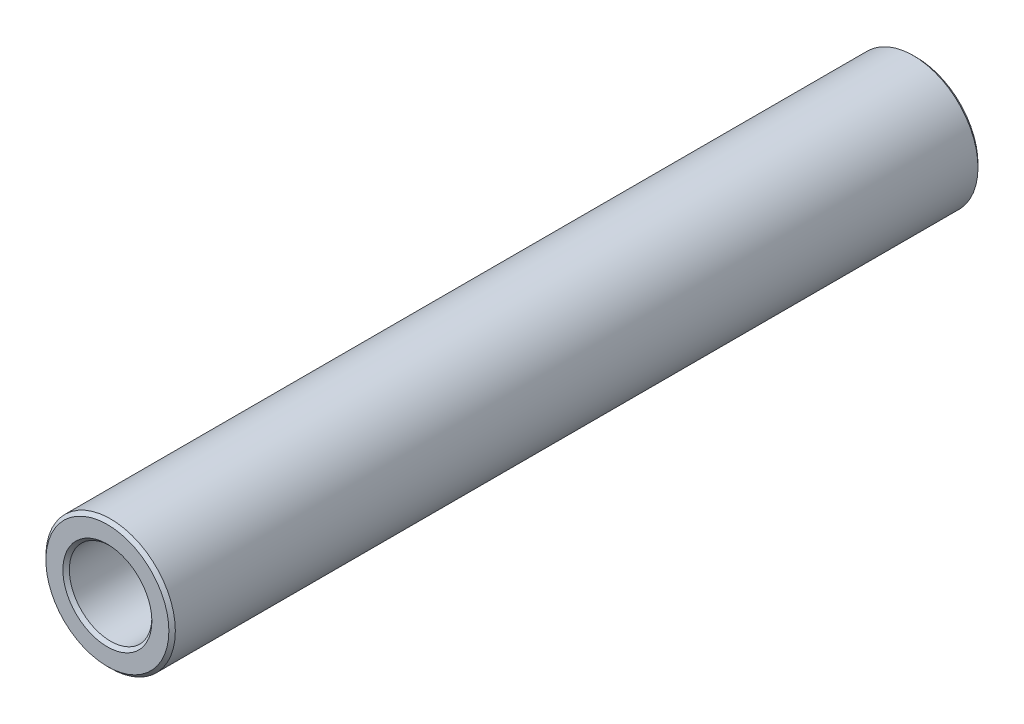
SolidWorks part; units mm, degrees
material "6061-T6 (SS)"
ref_plane "Front Plane" through (0, 0, 0) normal (0, 0, 1) x (1, 0, 0)
ref_plane "Top Plane" through (0, 0, 0) normal (0, 1, 0) x (1, 0, 0)
ref_plane "Right Plane" through (0, 0, 0) normal (1, 0, 0) x (0, 0, -1)
sketch "Sketch1" plane through (0, 0, 0) normal (0, 0, 1) x (1, 0, 0)
  circle A0 centre (0, 0) radius 2.55
  circle A1 centre (0, 0) radius 4
  dimension "D1" = 5.1
  dimension "D2" = 8
extrude "Boss-Extrude1" add sketch "Sketch1" along normal blind 50
chamfer "Chamfer1" distance 0.2 angle 45 4 edges at (4, 0, 0) (2.55, 0, 0) (2.55, 0, 50) (4, 0, 50)
